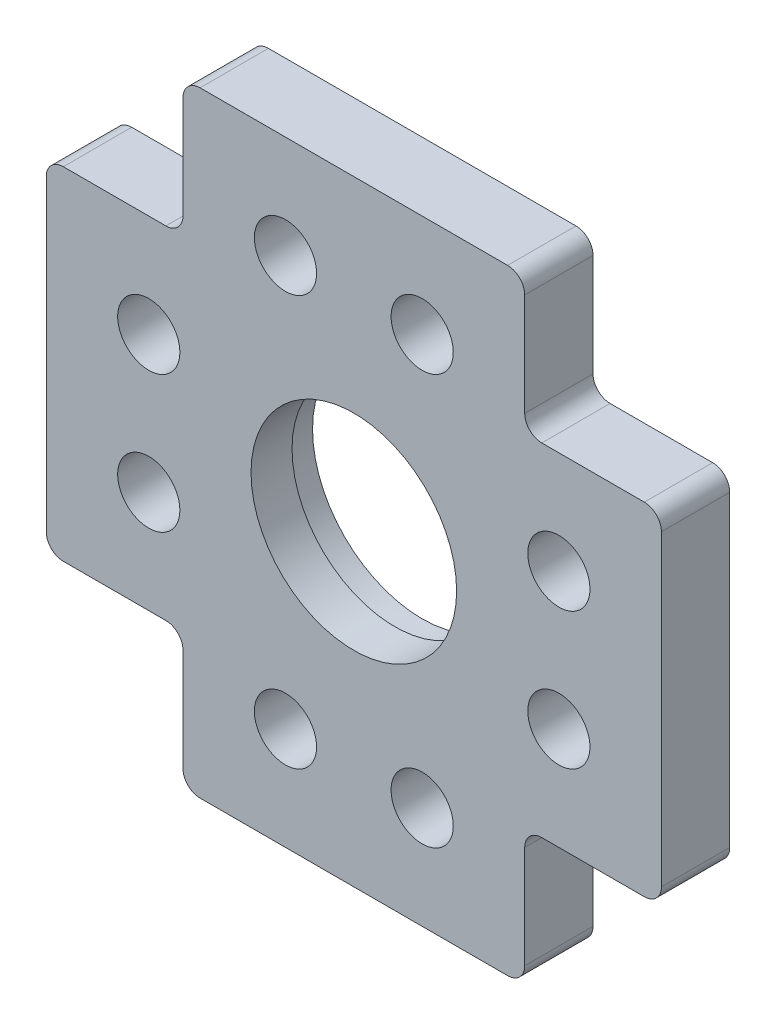
SolidWorks part; units mm, degrees
material "사용자정의 플라스틱"
ref_plane "정면" through (0, 0, 0) normal (0, 0, 1) x (1, 0, 0)
ref_plane "윗면" through (0, 0, 0) normal (0, 1, 0) x (1, 0, 0)
ref_plane "우측면" through (0, 0, 0) normal (1, 0, 0) x (0, 0, -1)
sketch "스케치1" plane through (0, 0, 0) normal (0, 0, 1) x (1, 0, 0)
  line L0 (-30.0091, 25) -> (-10.0091, 25)
  line L1 (-10.0091, 25) -> (-10.0091, 45)
  line L2 (-10.0091, 45) -> (39.9909, 45)
  line L3 (39.9909, 45) -> (39.9909, 25)
  line L4 (39.9909, 25) -> (59.9909, 25)
  line L5 (59.9909, 25) -> (59.9909, -25)
  line L6 (59.9909, -25) -> (39.9909, -25)
  line L7 (39.9909, -25) -> (39.9909, -45)
  line L8 (39.9909, -45) -> (-10.0091, -45)
  line L9 (-10.0091, -45) -> (-10.0091, -25)
  line L10 (-10.0091, -25) -> (-30.0091, -25)
  line L11 (-30.0091, -25) -> (-30.0091, 25)
  line L12 (-30.0091, 0) -> (59.9909, 0) construction
  line L13 (14.9909, 45) -> (14.9909, -45) construction
  circle A0 centre (14.9909, 0) radius 15.04
  point P20 (14.9909, 0)
  point P21 (14.9909, 0)
  point P22 (14.9909, 0)
  dimension "D1" = 30.08
  dimension "D2" = 20
  dimension "D3" = 50
  dimension "D5" = 50
  dimension "D6" = 20
  dimension "D7" = 50
  dimension "D8" = 20
  dimension "D9" = 20
  dimension "D10" = 20
  dimension "D11" = 20
  dimension "D12" = 50
extrude "보스-돌출1" add sketch "스케치1" along normal blind 10
fillet "필렛1" radius 2.5 4 edges at (39.9909, 25, 5) (39.9909, -25, 5) (-10.0091, -25, 5) (-10.0091, 25, 5)
sketch "스케치2" plane through (0, 0, 0) normal (0, 0, -1) x (-1, 0, 0)
  circle A0 centre (-14.9909, 0) radius 16.04
  circle A1 centre (-14.9909, 0) radius 15.04 construction
  dimension "D1" = 32.08
extrude "컷-돌출1" cut sketch "스케치2" against normal blind 4
fillet "필렛2" radius 2.5 8 edges at (-10.0091, 45, 5) (39.9909, 45, 5) (59.9909, 25, 5) (59.9909, -25, 5) (39.9909, -45, 5) (-10.0091, -45, 5) (-30.0091, -25, 5) (-30.0091, 25, 5)
sketch "스케치5" plane through (0, 0, 10) normal (0, 0, 1) x (1, 0, 0)
  circle A0 centre (-15.0091, -10) radius 4.55
  circle A1 centre (-15.0091, 10) radius 4.55
  circle A2 centre (14.9909, 0) radius 15.04 construction
  dimension "D3" = 9.1
  dimension "D4" = 9.1
  dimension "D5" = 30
  dimension "D6" = 30
  dimension "D1" = 10
  dimension "D2" = 10
extrude "컷-돌출2" cut sketch "스케치5" against normal through all
pattern_circular "원형 패턴1" count 4 over 360 about axis through (14.9909, 0, 0) along (0, 0, 1) of "컷-돌출2"
